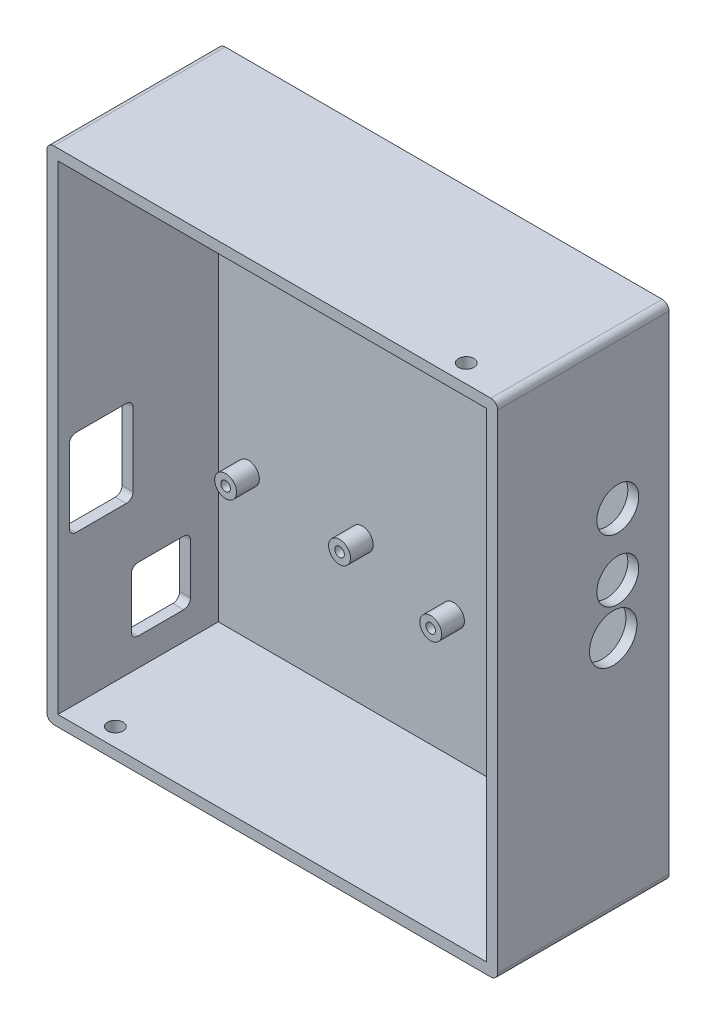
SolidWorks part; units mm, degrees
ref_plane "前视基准面" through (0, 0, 0) normal (0, 0, 1) x (1, 0, 0)
ref_plane "上视基准面" through (0, 0, 0) normal (0, 1, 0) x (1, 0, 0)
ref_plane "右视基准面" through (0, 0, 0) normal (1, 0, 0) x (0, 0, -1)
other "Configuration Table"
sketch "草图1" plane through (0, 0, 0) normal (0, 0, 1) x (1, 0, 0)
  line L0 (-2.5, -9.5) -> (93.4, -9.5)
  line L1 (94.9, -8) -> (94.9, 99)
  line L2 (93.4, 100.5) -> (-2.5, 100.5)
  line L3 (-4, 99) -> (-4, -8)
  arc A0 (93.4, -9.5) -> (94.9, -8) centre (93.4, -8) ccw
  arc A1 (94.9, 99) -> (93.4, 100.5) centre (93.4, 99) ccw
  arc A2 (-2.5, 100.5) -> (-4, 99) centre (-2.5, 99) ccw
  arc A3 (-4, -8) -> (-2.5, -9.5) centre (-2.5, -8) ccw
extrude "Floor_2p4mm" add sketch "草图1" along normal blind 2.4
sketch "草图2" plane through (0, 0, 0) normal (0, 0, 1) x (1, 0, 0)
  circle A0 centre (5, 24.5) radius 2.4
  circle A1 centre (5, 88) radius 2.4
  circle A2 centre (30, 24.5) radius 2.4
  circle A3 centre (30, 88) radius 2.4
  circle A4 centre (78, 12) radius 2.4
  circle A5 centre (50, 20) radius 2.4
extrude "Six_PCB_supports_5mm" add sketch "草图2" along normal blind 5 from offset 2.4
sketch "草图3" plane through (0, 0, 0) normal (0, 0, 1) x (1, 0, 0)
  line L0 (-2.5, -9.5) -> (93.4, -9.5)
  line L1 (94.9, -8) -> (94.9, 99)
  line L2 (93.4, 100.5) -> (-2.5, 100.5)
  line L3 (-4, 99) -> (-4, -8)
  line L4 (-1.6, -7.1) -> (92.5, -7.1)
  line L5 (92.5, -7.1) -> (92.5, 98.1)
  line L6 (92.5, 98.1) -> (-1.6, 98.1)
  line L7 (-1.6, 98.1) -> (-1.6, -7.1)
  arc A0 (93.4, -9.5) -> (94.9, -8) centre (93.4, -8) ccw
  arc A1 (94.9, 99) -> (93.4, 100.5) centre (93.4, 99) ccw
  arc A2 (-2.5, 100.5) -> (-4, 99) centre (-2.5, 99) ccw
  arc A3 (-4, -8) -> (-2.5, -9.5) centre (-2.5, -8) ccw
extrude "Integral_front_rear_and_side_walls" add sketch "草图3" along normal blind 35.2 from offset 2.4
sketch "草图4" plane through (0, 0, 0) normal (0, 0, 1) x (1, 0, 0)
  circle A0 centre (5, 24.5) radius 1.05
  circle A1 centre (5, 88) radius 1.05
  circle A2 centre (30, 24.5) radius 1.05
  circle A3 centre (30, 88) radius 1.05
  circle A4 centre (78, 12) radius 1.05
  circle A5 centre (50, 20) radius 1.05
extrude "Six_blind_M2p5_standoff_pilots" cut sketch "草图4" against normal blind 2.05 and the other way blind 2.05 from offset 5.35
sketch "草图5" plane through (0, 0, 0) normal (0, 1, 0) x (1, 0, 0)
  circle A0 centre (7, -33.6) radius 1.7
extrude "Side_lid_screw_1" cut sketch "草图5" against normal blind 1.25 and the other way blind 1.25 from offset 8.3
sketch "草图6" plane through (0, 0, 0) normal (0, 1, 0) x (1, 0, 0)
  circle A0 centre (84, -33.6) radius 1.7
extrude "Side_lid_screw_2" cut sketch "草图6" against normal blind 1.25 and the other way blind 1.25 from offset 99.3
sketch "草图7" plane through (0, 0, 0) normal (1, 0, 0) x (0, 0, -1)
  circle A0 centre (-12.25, 43.0009) radius 5.2
  circle A1 centre (-11.25, 53.5) radius 4.6
  circle A2 centre (-11.25, 67.1) radius 4.6
extrude "Front_audio_access" cut sketch "草图7" against normal blind 1.25 and the other way blind 1.25 from offset 93.7
sketch "草图8" plane through (0, 0, 0) normal (1, 0, 0) x (0, 0, -1)
  line L0 (-8.5, 0.5) -> (-8.5, 11.5)
  line L1 (-10, 13) -> (-20, 13)
  line L2 (-21.5, 11.5) -> (-21.5, 0.5)
  line L3 (-20, -1) -> (-10, -1)
  line L4 (-21.1, 27) -> (-21.1, 43)
  line L5 (-22.6, 44.5) -> (-33.6, 44.5)
  line L6 (-35.1, 43) -> (-35.1, 27)
  line L7 (-33.6, 25.5) -> (-22.6, 25.5)
  arc A0 (-8.5, 11.5) -> (-10, 13) centre (-10, 11.5) ccw
  arc A1 (-20, 13) -> (-21.5, 11.5) centre (-20, 11.5) ccw
  arc A2 (-21.5, 0.5) -> (-20, -1) centre (-20, 0.5) ccw
  arc A3 (-10, -1) -> (-8.5, 0.5) centre (-10, 0.5) ccw
  arc A4 (-21.1, 43) -> (-22.6, 44.5) centre (-22.6, 43) ccw
  arc A5 (-33.6, 44.5) -> (-35.1, 43) centre (-33.6, 43) ccw
  arc A6 (-35.1, 27) -> (-33.6, 25.5) centre (-33.6, 27) ccw
  arc A7 (-22.6, 25.5) -> (-21.1, 27) centre (-22.6, 27) ccw
extrude "Rear_DC_and_USB_access" cut sketch "草图8" against normal blind 1.25 and the other way blind 1.25 from offset 2.8
